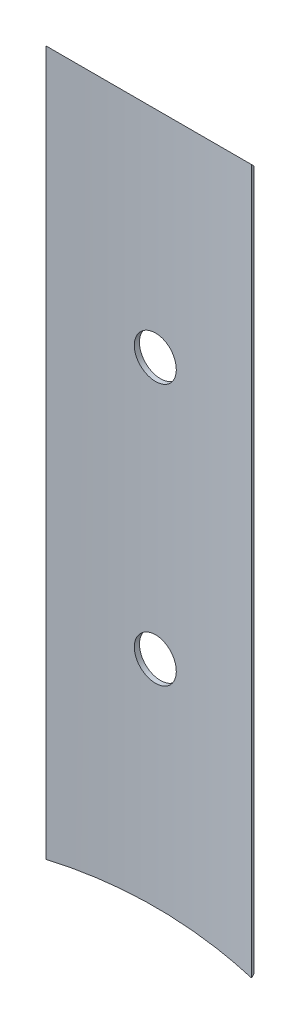
SolidWorks part; units mm, degrees
ref_plane "Front Plane" through (0, 0, 0) normal (0, 0, 1) x (1, 0, 0)
ref_plane "Top Plane" through (0, 0, 0) normal (0, 1, 0) x (1, 0, 0)
ref_plane "Right Plane" through (0, 0, 0) normal (1, 0, 0) x (0, 0, -1)
sketch "Sketch1" plane through (0, 0, 0) normal (0, 1, 0) x (1, 0, 0)
  line L0 (-9, 1) -> (9, 1)
  line L1 (9, 1) -> (9, 0.5)
  line L2 (9.5, 0) -> (11, 0)
  line L3 (11, -0.237) -> (11, 0)
  line L10 (0, -55) -> (0, 55) construction
  line L16 (-11, -0.237) -> (-11, 0)
  line L17 (-9.5, 0) -> (-11, 0)
  line L18 (-9, 1) -> (-9, 0.5)
  line L19 (-9, 0.5) -> (-9.5, 0)
  line L20 (9, 0.5) -> (9.5, 0)
  arc A0 (11, -0.237) -> (-11, -0.237) centre (0, -84.5222) ccw
  point P3 (9, 0)
  point P22 (-9, 0)
  point P24 (0, 1)
  point P28 (11, 0)
  point P29 (11, 0)
  point P30 (11, 0)
  dimension "D9" = 170
  dimension "D1" = 18
  dimension "D2" = 22
  dimension "D3" = 1
  dimension "D10" = 0.5
  dimension "D11" = 45
  dimension "D12" = 0.5
  dimension "D13" = 45
extrude "Boss-Extrude1" add sketch "Sketch1" along normal mid plane 80
chamfer "Chamfer1" [suppressed] distance 18 angle 45
chamfer "Chamfer2" [suppressed] distance 2 angle 45
sketch "Sketch4" plane through (0, 0, -1) normal (0, 0, -1) x (-1, 0, 0)
  line L0 (0.6803, 0) -> (-0.6803, 0) construction
  line L1 (0, 0.6803) -> (0, -0.6803) construction
  point P0 (0, 14)
  point P5 (0, -14)
  dimension "D1" = 28
sketch "Sketch6" plane through (0, 0, 0) normal (1, 0, 0) x (0, 0, -1)
  line L0 (1, -36.5) -> (1, 36.5)
  line L1 (1, 40) -> (1, -40) construction
  line L2 (1, 36.5) -> (-0.237, 37.737)
  line L3 (-0.237, 37.737) -> (-0.237, -37.737)
  line L4 (-0.237, -37.737) -> (1, -36.5)
  line L5 (-0.237, 40) -> (-0.237, -40) construction
  line L6 (0, 40) -> (0, -40) construction
  line L7 (0, 37.5) -> (0, -37.5) construction
  point P0 (-0.237, 0)
  point P5 (1, 0)
  point P10 (1, 46.2676)
  point P11 (1, 0)
  point P13 (0, 0)
  dimension "D1" = 45
  dimension "D2" = 1
  dimension "D3" = 75
extrude "Cut-Extrude1" cut sketch "Sketch6" against normal through all both and the other way through all flip side to cut
hole_wizard "M4 Clearance Hole1" positions "Sketch4" profile "Sketch3" hole size "M4" standard "ISO" end condition through all
sketch "Sketch3" plane through (0, 14, -1) normal (1, 0, 0) x (0, 1, 0)
  line L0 (0, 0) -> (0, 1.237)
  line L1 (0, 1.237) -> (2.25, 1.237)
  line L2 (2.25, 1.237) -> (2.25, 0)
  line L5 (2.25, 0) -> (0, 0)
  line L11 (0, -6.35) -> (0, 107.95) construction
  dimension "Thru Hole Dia." = 4.5
  dimension "Thru Hole Depth" = 1.237
